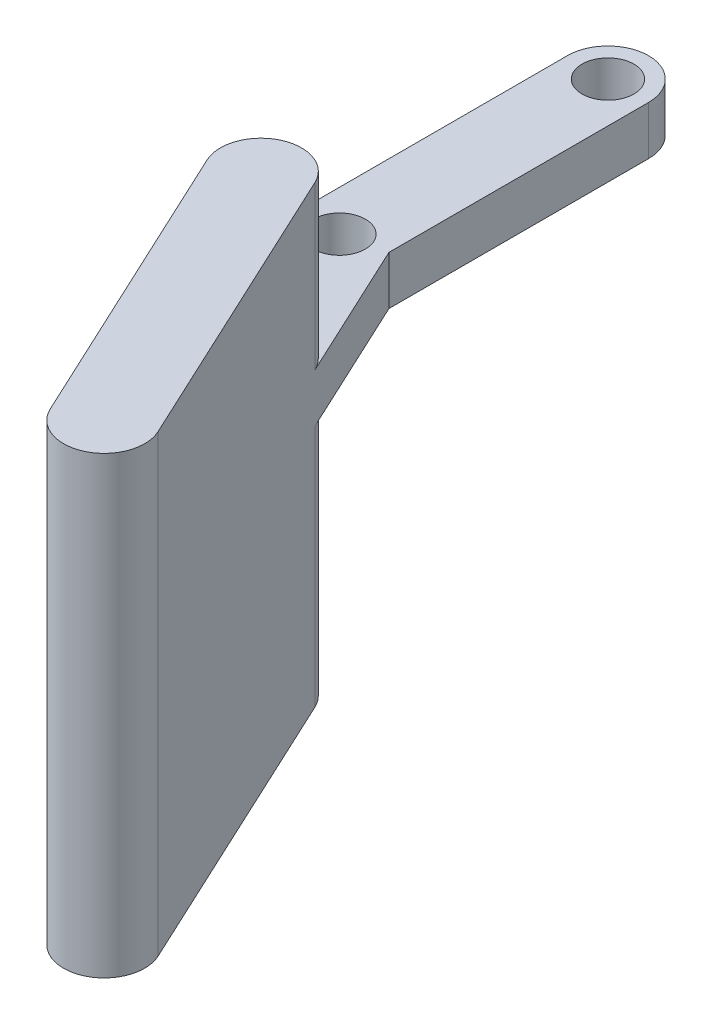
SolidWorks part; units mm, degrees
ref_plane "Front Plane" through (0, 0, 0) normal (0, 0, 1) x (1, 0, 0)
ref_plane "Top Plane" through (0, 0, 0) normal (0, 1, 0) x (1, 0, 0)
ref_plane "Right Plane" through (0, 0, 0) normal (1, 0, 0) x (0, 0, -1)
sketch "Sketch1" plane through (0, 0, 0) normal (0, 1, 0) x (1, 0, 0)
  line L0 (0, 0) -> (0, -16.5529) construction
  line L1 (2.5, 0) -> (2.5, -16.5529)
  line L2 (-2.5, 0) -> (-2.5, -16.5529)
  arc A0 (2.5, 0) -> (-2.5, 0) centre (0, 0) ccw
  arc A1 (-2.5, -16.5529) -> (2.5, -16.5529) centre (0, -16.5529) ccw
  point P3 (0, -8.2765)
  dimension "D1" = 2.5
  dimension "D2" = 16.5529
extrude "Boss-Extrude1" add sketch "Sketch1" along normal blind 3
sketch "Sketch2" plane through (0, 3, 0) normal (0, 1, 0) x (1, 0, 0)
  line L0 (0, -16.5529) -> (12.6866, -43.7384) construction
  line L1 (2.2655, -15.4957) -> (14.952, -42.6812)
  line L2 (-2.2655, -17.6102) -> (10.4211, -44.7957)
  line L3 (0, 0) -> (7.7578, 0) construction
  arc A0 (2.2655, -15.4957) -> (-2.2655, -17.6102) centre (0, -16.5529) ccw
  arc A1 (10.4211, -44.7957) -> (14.952, -42.6812) centre (12.6866, -43.7384) ccw
  point P3 (6.3433, -30.1457)
  dimension "D1" = 2.5
  dimension "D2" = 30
  dimension "D3" = 64.983
extrude "Boss-Extrude2" add sketch "Sketch2" against normal blind 3
sketch "Sketch3" plane through (0, 3, 0) normal (0, 1, 0) x (1, 0, 0)
  circle A0 centre (0, 0) radius 1.6
  circle A1 centre (0, -16.5529) radius 1.6
  dimension "D1" = 3.2
  dimension "D2" = 3.2
extrude "Cut-Extrude1" cut sketch "Sketch3" against normal through all
sketch "Sketch5" plane through (0, 0, 0) normal (0, -1, 0) x (1, 0, 0)
  line L0 (12.6866, 43.7384) -> (4.2289, 25.6148) construction
  line L1 (14.952, 42.6812) -> (6.4943, 24.5576)
  line L2 (10.4211, 44.7957) -> (1.9634, 26.672)
  line L3 (0, 0) -> (9.3795, 0) construction
  arc A0 (14.952, 42.6812) -> (10.4211, 44.7957) centre (12.6866, 43.7384) ccw
  arc A1 (1.9634, 26.672) -> (6.4943, 24.5576) centre (4.2289, 25.6148) ccw
  point P3 (8.4577, 34.6766)
  dimension "D3" = 2.5
  dimension "D1" = 64.983
  dimension "D2" = 20
extrude "Boss-Extrude3" add sketch "Sketch5" along normal blind 15
sketch "Sketch6" plane through (0, 3, 0) normal (0, 1, 0) x (1, 0, 0)
  line L0 (12.6866, -43.7384) -> (4.2289, -25.6148) construction
  line L3 (10.4211, -44.7957) -> (1.9634, -26.672)
  line L4 (14.952, -42.6812) -> (6.4943, -24.5576)
  line L5 (-2.2655, -17.6102) -> (10.4211, -44.7957) construction
  arc A2 (10.4211, -44.7957) -> (14.952, -42.6812) centre (12.6866, -43.7384) ccw
  arc A3 (6.4943, -24.5576) -> (1.9634, -26.672) centre (4.2289, -25.6148) ccw
  point P2 (8.4577, -34.6766)
  dimension "D1" = 2.5
  dimension "D2" = 20
extrude "Boss-Extrude4" add sketch "Sketch6" along normal blind 10
